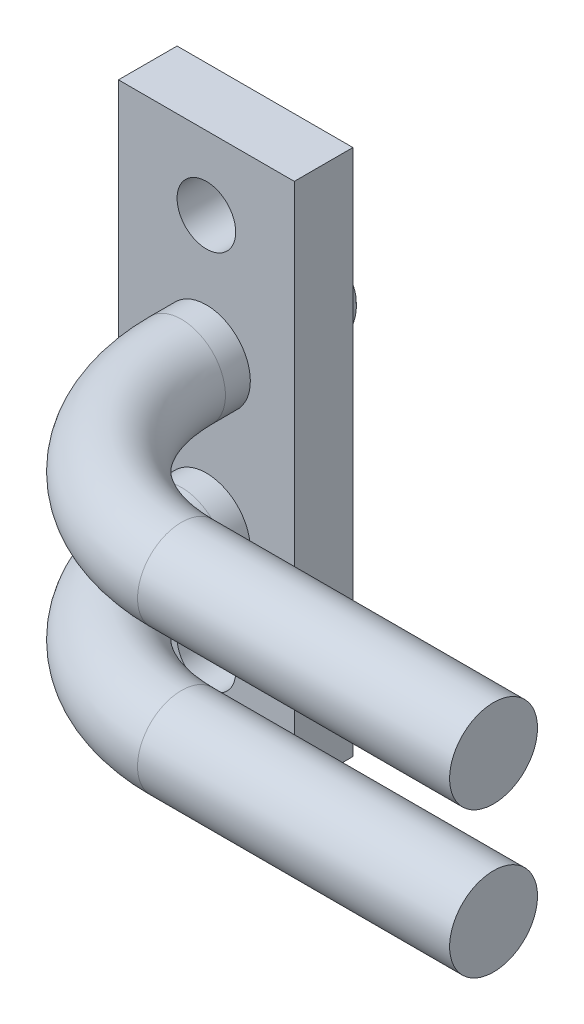
SolidWorks part; units mm, degrees
ref_plane "Front Plane" through (0, 0, 0) normal (0, 0, 1) x (1, 0, 0)
ref_plane "Top Plane" through (0, 0, 0) normal (0, 1, 0) x (1, 0, 0)
ref_plane "Right Plane" through (0, 0, 0) normal (1, 0, 0) x (0, 0, -1)
sketch "Sketch1" plane through (0, 0, 0) normal (0, 0, 1) x (1, 0, 0)
  line L1 (-3, -9) -> (3, -9)
  line L2 (-3, -9) -> (-3, 9)
  line L3 (-3, 9) -> (3, 9)
  line L4 (3, -9) -> (3, 9)
  line L5 (-3, -9) -> (3, 9) construction
  line L6 (-3, 9) -> (3, -9) construction
  point P0 (0, 0)
  dimension "D1" = 18
  dimension "D2" = 6
extrude "Boss-Extrude1" add sketch "Sketch1" along normal blind 2
sketch "Sketch2" plane through (0, 0, 0) normal (0, 0, -1) x (-1, 0, 0)
  circle A0 centre (0, 2.35) radius 1.5
  circle A1 centre (0, -2.62) radius 1.5
  dimension "D2" = 3
  dimension "D1" = 4.97
  dimension "D3" = 2.35
extrude "Boss-Extrude2" add sketch "Sketch2" along normal blind 2.5
sketch "Sketch6" plane through (-3, 0, 0) normal (-1, 0, 0) x (0, 0, 1)
  line L0 (0, 9) -> (0, -9) construction
  line L1 (-4.7845, -0.5369) -> (-2.1, -0.5369)
  line L2 (-4.7845, -0.5369) -> (-4.7845, -5.8804)
  line L3 (-4.7845, -5.8804) -> (-2.1, -5.8804)
  line L4 (-2.1, -0.5369) -> (-2.1, -5.8804)
  dimension "D1" = 2.1
extrude "Cut-Extrude2" cut sketch "Sketch6" against normal blind 10
fillet "Fillet1" radius 1.5 2 edges at (-1.5, 2.35, -2.5) (0, -4.12, -2.1)
sketch "Sketch3" plane through (0, 0, 2) normal (0, 0, 1) x (1, 0, 0)
  circle A0 centre (0, -2.62) radius 1.5 construction
  circle A1 centre (0, 2.35) radius 1.5 construction
  circle A2 centre (0, -2.62) radius 1.5
  circle A3 centre (0, 2.35) radius 1.5
ref_plane "Plane1" through (0, 2.35, 0) normal (0, 1, 0) x (-1, 0, 0)
sketch "Sketch4" plane through (0, 2.35, 0) normal (0, 1, 0) x (-1, 0, 0)
  line L0 (0, 2) -> (0, 2.85)
  line L1 (1.5, 2) -> (-1.5, 2) construction
  line L2 (-6, 8.85) -> (-16.65, 8.85)
  arc A0 (0, 2.85) -> (-6, 8.85) centre (-6, 2.85) ccw
  point P8 (0, 8.85)
  dimension "D3" = 6
  dimension "D1" = 16.65
  dimension "D2" = 6.85
sweep "Sweep1" add profiles "Sketch3" path "Sketch4"
sketch "Sketch5" plane through (0, 0, 2) normal (0, 0, 1) x (1, 0, 0)
  line L0 (0, 0) -> (3, 0) construction
  line L1 (3, -9) -> (3, 9) construction
  line L2 (0, -6.5) -> (0, 6.5) construction
  line L3 (3, 9) -> (-3, 9) construction
  circle A0 centre (0, 6.5) radius 1
  circle A1 centre (0, -6.5) radius 1
  dimension "D1" = 2
  dimension "D2" = 2.5
extrude "Cut-Extrude1" cut sketch "Sketch5" against normal through all
